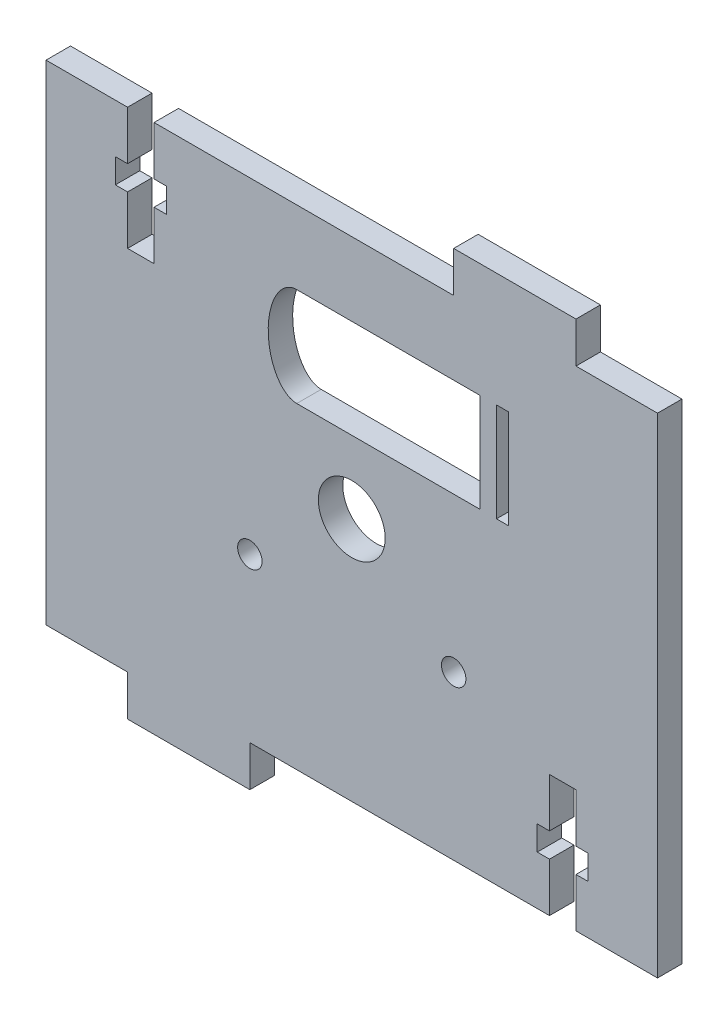
SolidWorks part; units mm, degrees
ref_plane "Plan de face" through (0, 0, 0) normal (0, 0, 1) x (1, 0, 0)
ref_plane "Plan de dessus" through (0, 0, 0) normal (0, 1, 0) x (1, 0, 0)
ref_plane "Plan de droite" through (0, 0, 0) normal (1, 0, 0) x (0, 0, -1)
sketch "Esquisse1" plane through (0, 0, 0) normal (0, 0, 1) x (1, 0, 0)
  line L0 (0, 0) -> (10, 0)
  line L1 (10, 0) -> (10, -5)
  line L2 (10, -5) -> (25, -5)
  line L3 (25, -5) -> (25, 0)
  line L4 (25, 0) -> (61.75, 0)
  line L5 (61.75, 0) -> (61.75, 6)
  line L6 (61.75, 6) -> (60.25, 6)
  line L7 (60.25, 6) -> (60.25, 9)
  line L8 (60.25, 9) -> (61.75, 9)
  line L9 (61.75, 9) -> (61.75, 15)
  line L10 (61.75, 15) -> (65, 15)
  line L11 (65, 15) -> (65, 9)
  line L12 (65, 9) -> (66.5, 9)
  line L13 (66.5, 9) -> (66.5, 6)
  line L14 (66.5, 6) -> (65, 6)
  line L15 (65, 6) -> (65, 0)
  line L16 (65, 0) -> (75, 0)
  line L17 (75, 0) -> (75, 60)
  line L18 (75, 60) -> (65, 60)
  line L19 (65, 60) -> (65, 65)
  line L20 (65, 65) -> (50, 65)
  line L21 (50, 65) -> (50, 60)
  line L22 (50, 60) -> (13.25, 60)
  line L23 (13.25, 60) -> (13.25, 54)
  line L24 (13.25, 54) -> (14.75, 54)
  line L25 (14.75, 54) -> (14.75, 51)
  line L26 (14.75, 51) -> (13.25, 51)
  line L27 (13.25, 51) -> (13.25, 45)
  line L28 (13.25, 45) -> (10, 45)
  line L29 (10, 45) -> (10, 51)
  line L30 (10, 51) -> (8.5, 51)
  line L31 (8.5, 51) -> (8.5, 54)
  line L32 (8.5, 54) -> (10, 54)
  line L33 (10, 54) -> (10, 60)
  line L34 (10, 60) -> (0, 60)
  line L35 (0, 60) -> (0, 0)
  line L36 (37.5, 30) -> (128.8325, 30) construction
  line L37 (37.5, 30) -> (37.5, -6.9069) construction
  line L38 (30.75, 38.9) -> (53.25, 38.9)
  line L39 (30.75, 38.9) -> (30.75, 51) construction
  line L40 (30.75, 51) -> (53.25, 51)
  line L41 (53.25, 38.9) -> (53.25, 51)
  line L42 (55.25, 51) -> (56.75, 51)
  line L43 (55.25, 51) -> (55.25, 38.9)
  line L44 (55.25, 38.9) -> (56.75, 38.9)
  line L45 (56.75, 51) -> (56.75, 38.9)
  circle A0 centre (37.5, 30) radius 4.1
  circle A1 centre (25, 20) radius 1.5
  circle A2 centre (50, 20) radius 1.5
  ellipse E0 centre (30.75, 44.95) end of major axis (30.75, 38.9) minor radius 3.5 (30.75, 51) -> (30.75, 38.9) ccw
  point P56 (50, 20)
  dimension "D14" = 8.2
  dimension "D22" = 3
  dimension "D1" = 6
  dimension "D2" = 6
  dimension "D3" = 3
  dimension "D4" = 60
  dimension "D5" = 5
  dimension "D6" = 36.75
  dimension "D7" = 10
  dimension "D8" = 3.25
  dimension "D9" = 15
  dimension "D10" = 1.5
  dimension "D11" = 10
  dimension "D12" = 37.5
  dimension "D13" = 30
  dimension "D15" = 15.75
  dimension "D16" = 12.1
  dimension "D17" = 22.5
  dimension "D18" = 8.9
  dimension "D19" = 3.5
  dimension "D20" = 1.5
  dimension "D21" = 2
  dimension "D23" = 12.5
  dimension "D24" = 10
extrude "Boss.-Extru.1" add sketch "Esquisse1" along normal blind 3
